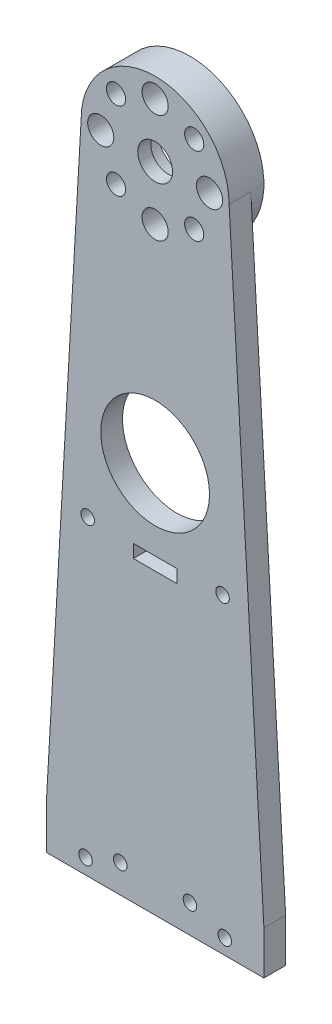
SolidWorks part; units mm, degrees
ref_plane "Front Plane" through (0, 0, 0) normal (0, 0, 1) x (1, 0, 0)
ref_plane "Top Plane" through (0, 0, 0) normal (0, 1, 0) x (1, 0, 0)
ref_plane "Right Plane" through (0, 0, 0) normal (1, 0, 0) x (0, 0, -1)
sketch "Sketch1" plane through (0, 0, 0) normal (0, 0, 1) x (1, 0, 0)
  line L0 (-25, 0) -> (25, 0)
  line L1 (0, 0) -> (0, 150) construction
  line L4 (0, 150) -> (0, 90) construction
  line L6 (-25, 0) -> (-25, 10)
  line L8 (25, 10) -> (25, 0)
  line L9 (-17, 150) -> (-25, 10)
  line L10 (17, 150) -> (25, 10)
  line L11 (-25, 0) -> (-25, 3.5) construction
  line L12 (-25, 3.5) -> (-16, 3.5) construction
  line L13 (-16, 3.5) -> (16, 3.5) construction
  line L14 (-25, 10) -> (-25, 6.5) construction
  line L15 (-25, 6.5) -> (-8, 6.5) construction
  line L16 (-8, 6.5) -> (8, 6.5) construction
  line L17 (0, 90) -> (0, 71.5) construction
  line L20 (-5, 68.5) -> (-15.5, 68.5) construction
  line L21 (5, 68.5) -> (5, 71.5) construction
  line L22 (5, 68.5) -> (-5, 68.5)
  line L23 (-5, 68.5) -> (-5, 71.5)
  line L24 (-5, 71.5) -> (5, 71.5)
  line L25 (5, 71.5) -> (5, 68.5)
  line L26 (-15.5, 68.5) -> (-15.5, 71.5) construction
  line L27 (5, 68.5) -> (15.5, 68.5) construction
  line L28 (15.5, 68.5) -> (15.5, 71.5) construction
  circle A0 centre (0, 150) radius 4
  arc A1 (-17, 150) -> (17, 150) centre (0, 150) cw
  circle A2 centre (0, 90) radius 12.5
  circle A3 centre (-8, 6.5) radius 1.55
  circle A4 centre (-16, 3.5) radius 1.55
  circle A5 centre (8, 6.5) radius 1.55
  circle A6 centre (16, 3.5) radius 1.55
  circle A7 centre (-15.5, 71.5) radius 1.55
  circle A8 centre (15.5, 71.5) radius 1.55
  point P4 (0, 0)
  point P29 (0, 71.5)
  point P30 (0, 71.5)
extrude "Boss-Extrude1" add sketch "Sketch1" along normal blind 5
sketch "Sketch2" plane through (0, 0, 0) normal (0, 0, -1) x (-1, 0, 0)
  circle A0 centre (0, 150) radius 17
extrude "Boss-Extrude2" add sketch "Sketch2" along normal blind 3
sketch "Sketch3" plane through (0, 0, 5) normal (0, 0, 1) x (1, 0, 0)
  line L0 (0, 150) -> (8.9803, 158.9803) construction
  circle A0 centre (0, 150) radius 12.5 construction
  circle A1 centre (-12.5, 150) radius 1.55
  circle A2 centre (0, 162.5) radius 1.55
  circle A3 centre (12.5, 150) radius 1.55
  circle A4 centre (0, 137.5) radius 1.55
  circle A5 centre (0, 150) radius 12.7 construction
  circle A6 centre (8.9803, 158.9803) radius 1
  circle A7 centre (8.9803, 141.0197) radius 1
  circle A8 centre (-8.9803, 141.0197) radius 1
  circle A9 centre (-8.9803, 158.9803) radius 1
  point P14 (0, 150)
  point P24 (0, 150)
  dimension "D1" = 4
  dimension "D2" = 4
extrude "Cut-Extrude1" cut sketch "Sketch3" against normal blind 8
sketch "Sketch4" plane through (0, 0, 5) normal (0, 0, 1) x (1, 0, 0)
  circle A0 centre (-12.5, 150) radius 3
  circle A1 centre (0, 162.5) radius 3
  circle A2 centre (12.5, 150) radius 3
  circle A3 centre (0, 137.5) radius 3
  circle A4 centre (-8.9803, 158.9803) radius 2.2
  circle A5 centre (8.9803, 158.9803) radius 2.2
  circle A6 centre (8.9803, 141.0197) radius 2.2
  circle A7 centre (-8.9803, 141.0197) radius 2.2
  point P12 (0, 150)
  point P22 (0, 150)
  dimension "D1" = 4
  dimension "D2" = 4
extrude "Cut-Extrude2" cut sketch "Sketch4" against normal blind 4.5
sketch "Sketch5" plane through (0, 0, -3) normal (0, 0, -1) x (-1, 0, 0)
  circle A0 centre (0, 150) radius 8
extrude "Cut-Extrude3" cut sketch "Sketch5" against normal blind 5
